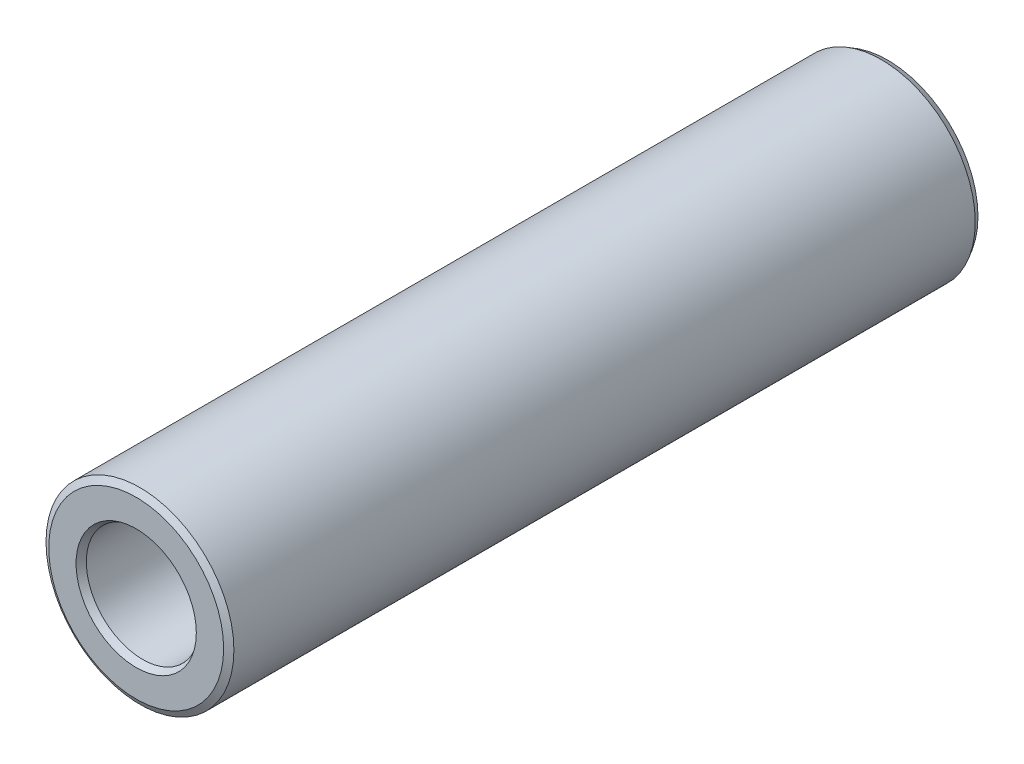
SolidWorks part; units mm, degrees
ref_plane "Front Plane" through (0, 0, 0) normal (0, 0, 1) x (1, 0, 0)
ref_plane "Top Plane" through (0, 0, 0) normal (0, 1, 0) x (1, 0, 0)
ref_plane "Right Plane" through (0, 0, 0) normal (1, 0, 0) x (0, 0, -1)
sketch "Sketch1" plane through (0, 0, 0) normal (0, 0, 1) x (1, 0, 0)
  circle A0 centre (0, 0) radius 2.5
  circle A1 centre (0, 0) radius 1.5
  dimension "D1" = 5
  dimension "D2" = 3
extrude "Boss-Extrude1" add sketch "Sketch1" along normal mid plane 20
chamfer "Chamfer1" distance 0.1 angle 60 4 edges at (1.5, 0, -10) (2.5, 0, -10) (1.5, 0, 10) (2.5, 0, 10)
